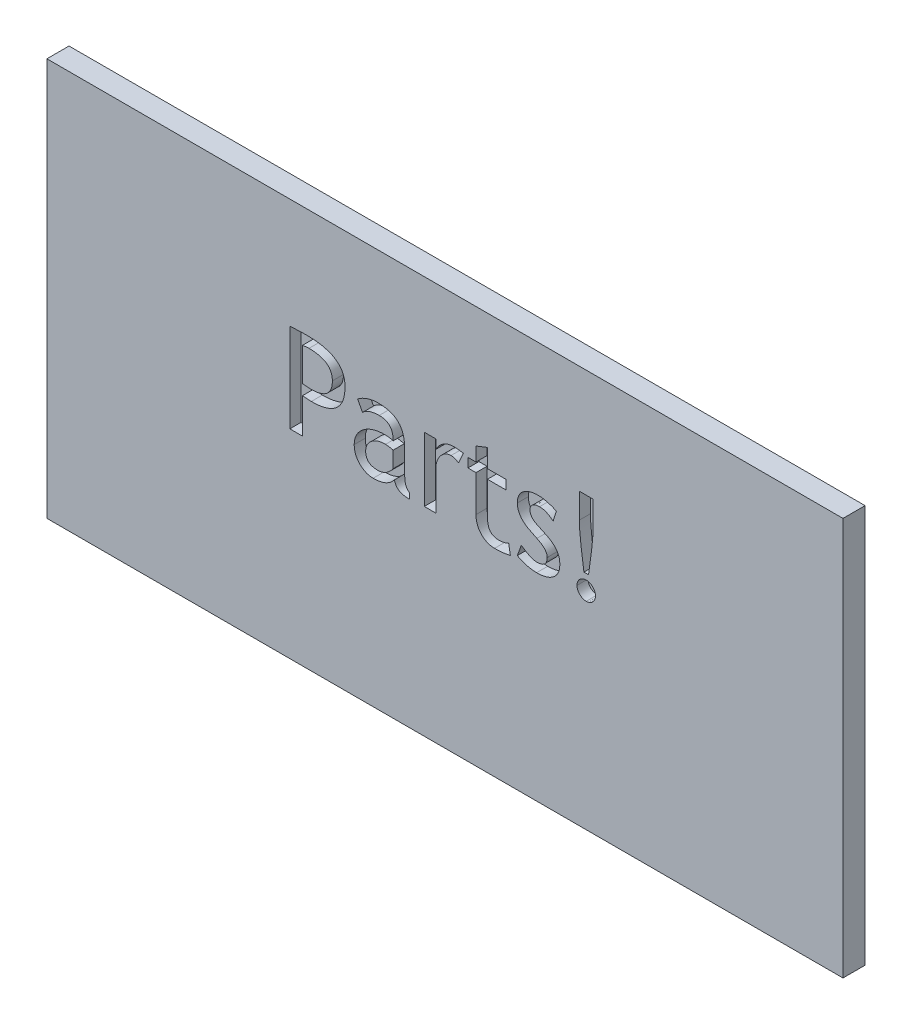
SolidWorks part; units mm, degrees
ref_plane "Front Plane" through (0, 0, 0) normal (0, 0, 1) x (1, 0, 0)
ref_plane "Top Plane" through (0, 0, 0) normal (0, 1, 0) x (1, 0, 0)
ref_plane "Right Plane" through (0, 0, 0) normal (1, 0, 0) x (0, 0, -1)
sketch "Sketch1" plane through (0, 0, 0) normal (0, 0, 1) x (1, 0, 0)
  line L1 (-457.2, -228.6) -> (457.2, -228.6)
  line L2 (-457.2, -228.6) -> (-457.2, 228.6)
  line L3 (-457.2, 228.6) -> (457.2, 228.6)
  line L4 (457.2, -228.6) -> (457.2, 228.6)
  line L5 (-457.2, -228.6) -> (457.2, 228.6) construction
  line L6 (-457.2, 228.6) -> (457.2, -228.6) construction
  point P0 (0, 0)
  dimension "D1" = 914.4
  dimension "D2" = 457.2
extrude "Boss-Extrude1" add sketch "Sketch1" along normal blind 25.4
sketch "Sketch2" plane through (0, 0, 25.4) normal (0, 0, 1) x (1, 0, 0)
  line L0 (-457.2, 0) -> (457.2, 0) construction
  line L1 (-457.2, 228.6) -> (-457.2, -228.6) construction
  line L2 (457.2, -228.6) -> (457.2, 228.6) construction
  text T0 "Parts!" font "Trebuchet MS" height 101.6
extrude "Cut-Extrude1" cut sketch "Sketch2" against normal blind 12.7
